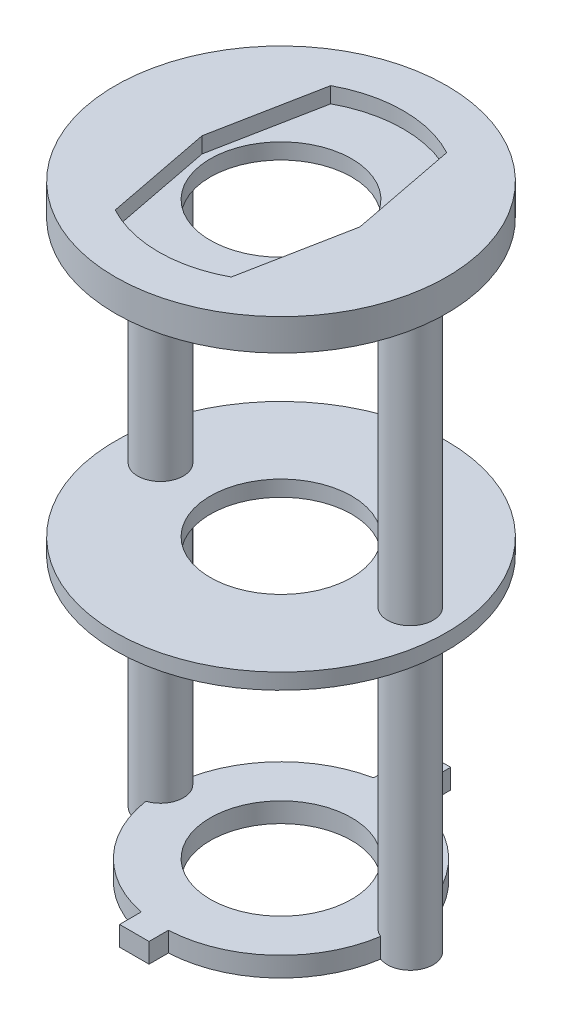
SolidWorks part; units mm, degrees
material "ABS"
ref_plane "Front Plane" through (0, 0, 0) normal (0, 0, 1) x (1, 0, 0)
ref_plane "Top Plane" through (0, 0, 0) normal (0, 1, 0) x (1, 0, 0)
ref_plane "Right Plane" through (0, 0, 0) normal (1, 0, 0) x (0, 0, -1)
sketch "Sketch2" plane through (0, 0, 0) normal (0, 1, 0) x (1, 0, 0)
  line L0 (0.7356, 15.0024) -> (0.7356, 20.7598)
  line L1 (0.7356, 20.7598) -> (-2.993, 20.7598)
  line L2 (-2.993, 20.7598) -> (-2.993, 14.7192)
  line L3 (-2.993, -14.7192) -> (-2.993, -17.4564)
  line L4 (-2.993, -17.4564) -> (0.7356, -17.4564)
  line L5 (0.7356, -17.4564) -> (0.7356, -15.0024)
  arc A0 (-2.993, 14.7192) -> (-14.6822, 3.1694) centre (0, 0) ccw
  arc A1 (-14.6822, 3.1694) -> (-14.8463, -2.2805) centre (-15.741, 0.4739) ccw
  arc A2 (-14.8463, -2.2805) -> (-2.993, -14.7192) centre (0, 0) ccw
  arc A3 (0.7356, -15.0024) -> (14.8548, -2.2241) centre (0, 0) ccw
  arc A4 (14.8548, -2.2241) -> (14.6961, 3.1045) centre (15.9072, 0.4739) ccw
  arc A5 (14.6961, 3.1045) -> (0.7356, 15.0024) centre (0, 0) ccw
  circle A6 centre (0, 0) radius 8.955
  circle A7 centre (-15.741, 0.4739) radius 1.715
  circle A8 centre (15.9072, 0.4739) radius 1.715
  dimension "D1" = 17.91
  dimension "D2" = 3.43
  dimension "D3" = 3.43
extrude "Boss-Extrude1" add sketch "Sketch2" against normal blind 2.5 contours A4 A5 L0 L1 L2 A0 A1 A2 L3 L4 L5 A3 A8 A7 A6
sketch "Sketch3" plane through (0, 0, 0) normal (0, 1, 0) x (1, 0, 0)
  circle A0 centre (-15.741, 0.4739) radius 2.896
  circle A1 centre (15.9072, 0.4739) radius 2.896
  circle M1 centre (15.9072, 0.4739) radius 1.715
  arc M4 (14.8548, -2.2241) -> (14.6961, 3.1045) centre (15.9072, 0.4739) ccw
extrude "Boss-Extrude2" add sketch "Sketch3" along normal blind 70.305 contours A1 M4 M1 | M1 | A0
sketch "Sketch4" plane through (0, 70.305, 0) normal (0, 1, 0) x (1, 0, 0)
  circle A0 centre (0, 0) radius 8.955
  circle A1 centre (0, 0) radius 21
  dimension "D1" = 42
extrude "Boss-Extrude3" add sketch "Sketch4" along normal blind 4
sketch "Sketch5" plane through (0, 74.305, 0) normal (0, 1, 0) x (1, 0, 0)
  line L0 (0, -0.0035) -> (-7.35, -0.0035) construction
  line L1 (-7.35, 13.6465) -> (-10, -0.0035)
  line L2 (-10, -0.0035) -> (-7.35, -13.6535)
  line L3 (7.35, -13.6535) -> (10, -0.0035)
  line L4 (10, -0.0035) -> (7.35, 13.6465)
  arc A0 (-7.35, 13.6465) -> (7.35, 13.6465) centre (0, 0) cw
  arc A1 (-7.35, -13.6535) -> (7.35, -13.6535) centre (0, -0.007) ccw
  dimension "D1" = 10
  dimension "D2" = 10
extrude "Cut-Extrude1" cut sketch "Sketch5" against normal blind 2
ref_plane "Plane1" through (0, 35.305, 0) normal (0, -1, 0) x (-1, 0, 0)
sketch "Sketch6" plane through (0, 35.305, 0) normal (0, -1, 0) x (-1, 0, 0)
  circle A0 centre (0, 0) radius 8.955
  circle A1 centre (0, 0) radius 21
extrude "Boss-Extrude4" add sketch "Sketch6" along normal blind 2
sketch "Sketch7" plane through (0, -2.5, 0) normal (0, -1, 0) x (1, 0, 0)
  circle A0 centre (-15.741, -0.4739) radius 1.715
  circle A1 centre (15.9072, -0.4739) radius 1.715
extrude "Cut-Extrude2" cut sketch "Sketch7" against normal blind 15
